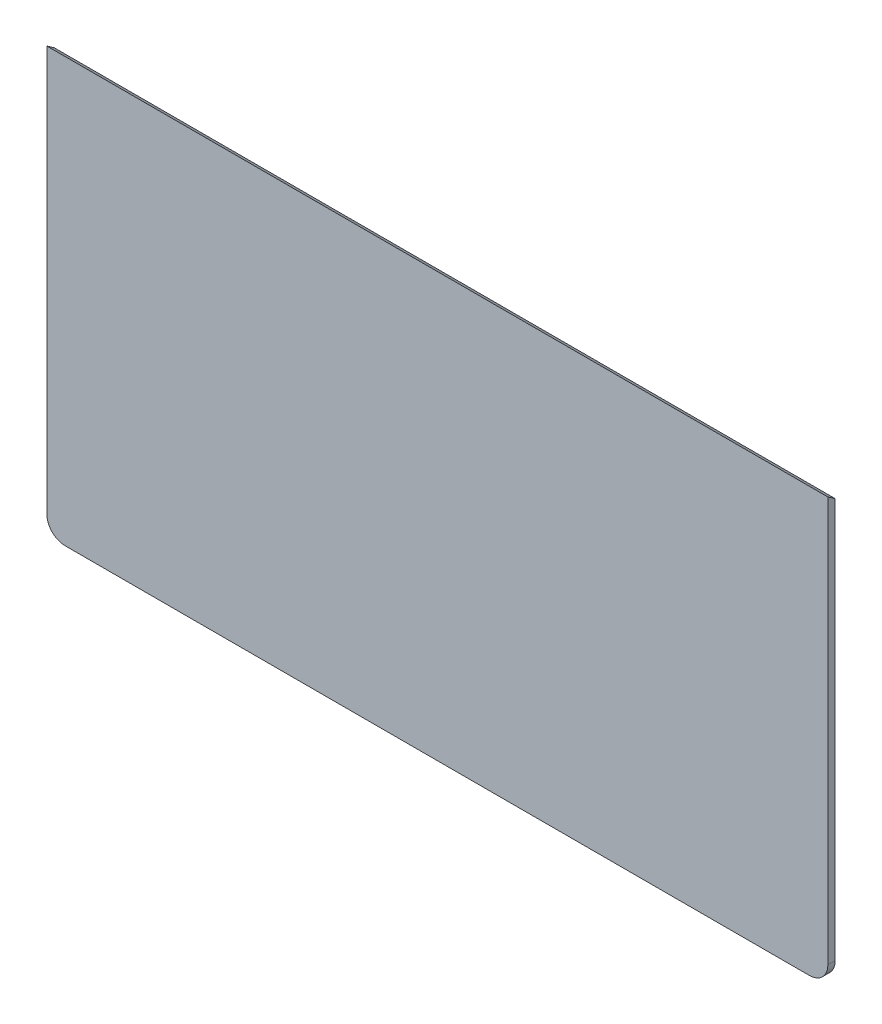
SolidWorks part; units mm, degrees
material "AISI 304"
ref_plane "Спереди" through (0, 0, 0) normal (0, 0, 1) x (1, 0, 0)
ref_plane "Сверху" through (0, 0, 0) normal (0, 1, 0) x (1, 0, 0)
ref_plane "Справа" through (0, 0, 0) normal (1, 0, 0) x (0, 0, -1)
sketch "Эскиз1" plane through (0, 0, 0) normal (0, 0, 1) x (1, 0, 0)
  line L1 (-212, -115) -> (212, -115)
  line L2 (-212, -115) -> (-212, 115)
  line L3 (-212, 115) -> (212, 115)
  line L4 (212, -115) -> (212, 115)
  line L5 (-212, -115) -> (212, 115) construction
  line L6 (-212, 115) -> (212, -115) construction
  point P0 (0, 0)
  dimension "D1" = 424
  dimension "D2" = 230
extrude "Бобышка-Вытянуть1" add sketch "Эскиз1" along normal blind 4
fillet "Скругление1" radius 10 2 edges at (212, -115, 2) (-212, -115, 2)
sketch "Эскиз2" plane through (212, 0, 0) normal (1, 0, 0) x (0, 0, -1)
  line L0 (-4, 115) -> (0, 112.1992)
  line L2 (0, 112.1992) -> (0, 115)
  line L3 (0, 115) -> (-4, 115)
  line L7 (0, -105) -> (0, 115) construction
  line L8 (-4, 115) -> (0, 115) construction
  dimension "D1" = 35
extrude "Вырез-Вытянуть1" cut sketch "Эскиз2" against normal through all
